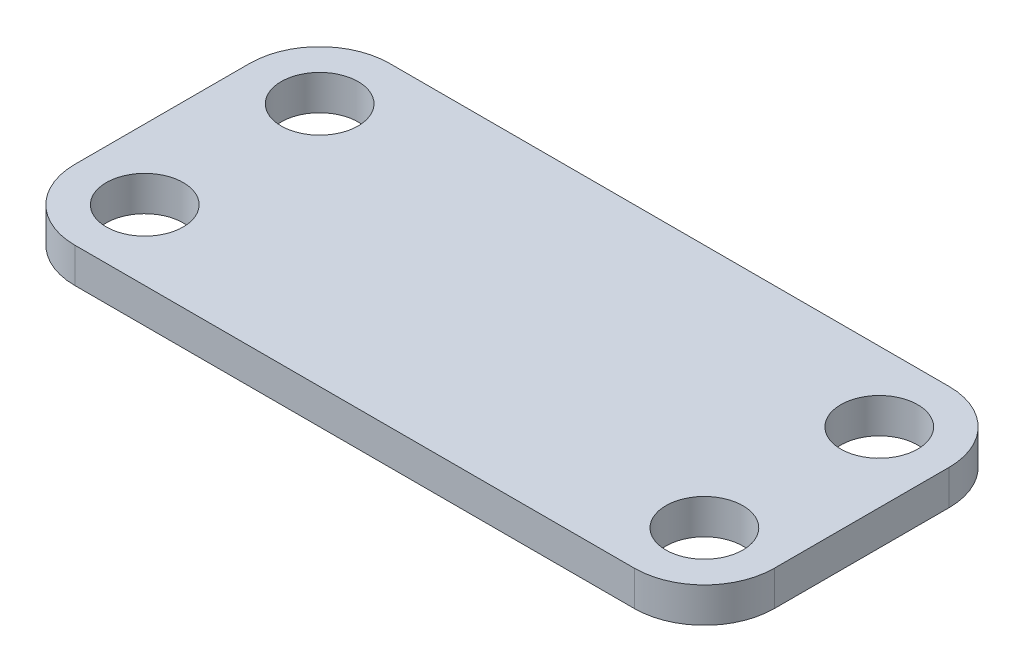
SolidWorks part; units mm, degrees
ref_plane "前视基准面" through (0, 0, 0) normal (0, 0, 1) x (1, 0, 0)
ref_plane "上视基准面" through (0, 0, 0) normal (0, 1, 0) x (1, 0, 0)
ref_plane "右视基准面" through (0, 0, 0) normal (1, 0, 0) x (0, 0, -1)
sketch "草图1" plane through (0, 0, 0) normal (0, 1, 0) x (1, 0, 0)
  line L1 (-10, 4.5) -> (10, 4.5)
  line L2 (-10, 4.5) -> (-10, -4.5)
  line L3 (-10, -4.5) -> (10, -4.5)
  line L4 (10, 4.5) -> (10, -4.5)
  line L5 (-10, 4.5) -> (10, -4.5) construction
  line L6 (-10, -4.5) -> (10, 4.5) construction
  point P0 (0, 0)
  dimension "D1" = 20
  dimension "D2" = 9
extrude "凸台-拉伸1" add sketch "草图1" along normal blind 1
hole_wizard "M2 间隙孔1" positions "草图2" profile "草图3" hole size "M2" standard "GB"
sketch "草图2" plane through (0, 1, 0) normal (0, 1, 0) x (1, 0, 0)
  line L1 (-8, 2.5) -> (8, 2.5)
  line L2 (-8, 2.5) -> (-8, -2.5)
  line L3 (-8, -2.5) -> (8, -2.5)
  line L4 (8, 2.5) -> (8, -2.5)
  line L5 (-8, 2.5) -> (8, -2.5)
  point P0 (-8, 2.5)
  point P2 (8, 2.5)
  point P4 (8, -2.5)
  point P6 (-8, -2.5)
  dimension "D1" = 5
  dimension "D2" = 16
sketch "草图3" plane through (-8, 1, -2.5) normal (1, 0, 0) x (0, 0, 1)
  line L0 (0, 0) -> (0, 8.1609)
  line L1 (0, 8.1609) -> (1.1, 7.5)
  line L2 (1.1, 7.5) -> (1.1, 0)
  line L5 (1.1, 0) -> (0, 0)
  line L10 (0, 8.1609) -> (-1.1, 7.5) construction
  line L11 (0, -6.35) -> (0, 107.95) construction
  dimension "孔直径" = 2.2
  dimension "孔深度" = 7.5
  dimension "导头角度" = 118
fillet "圆角1" radius 2 4 edges at (10, 0.5, 4.5) (10, 0.5, -4.5) (-10, 0.5, 4.5) (-10, 0.5, -4.5)
